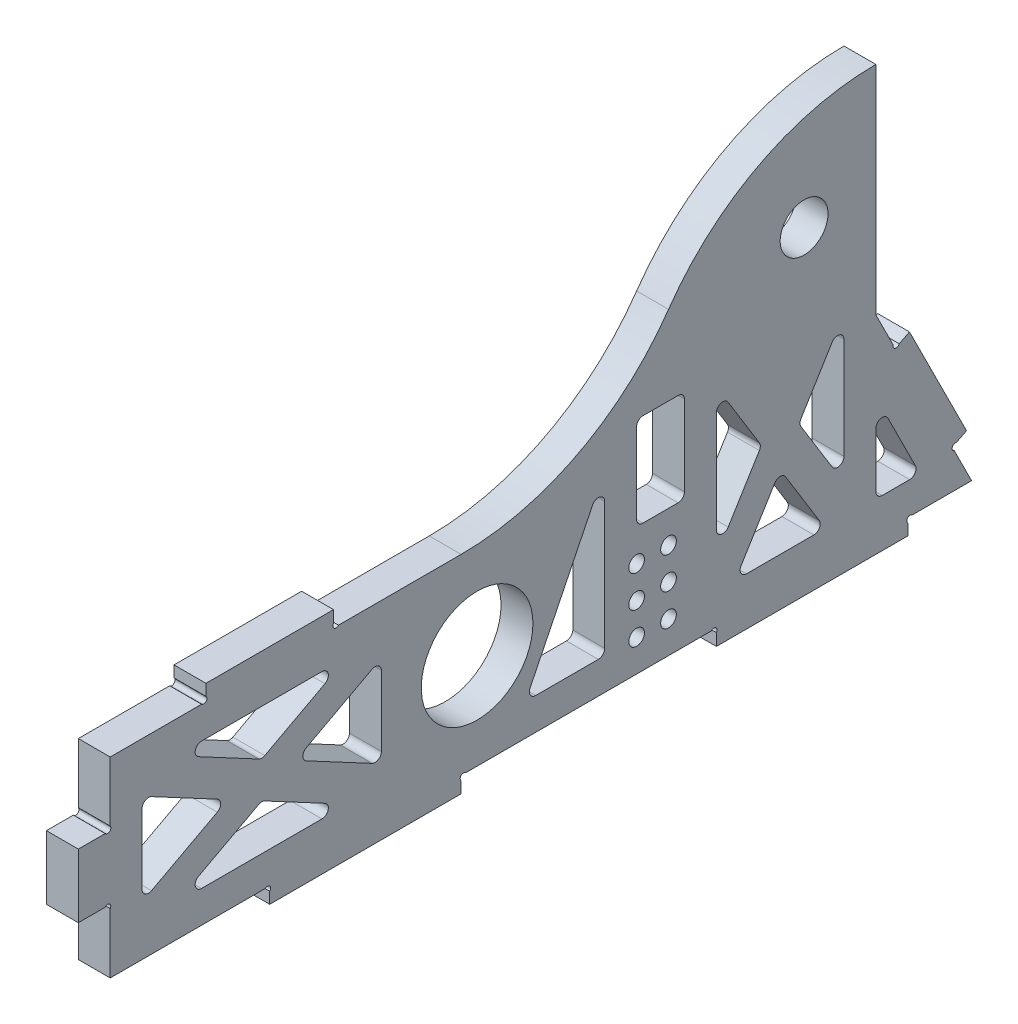
SolidWorks part; units mm, degrees
ref_plane "Front Plane" through (0, 0, 0) normal (0, 0, 1) x (1, 0, 0)
ref_plane "Top Plane" through (0, 0, 0) normal (0, 1, 0) x (1, 0, 0)
ref_plane "Right Plane" through (0, 0, 0) normal (1, 0, 0) x (0, 0, -1)
sketch "Sketch1" plane through (0, 0, 0) normal (1, 0, 0) x (0, 0, -1)
  line L0 (139.7, 38.1) -> (139.7, 124.46)
  line L1 (-177.8, -38.1) -> (177.8, -38.1)
  line L2 (-177.8, -38.1) -> (-177.8, 38.1)
  line L3 (-177.8, 38.1) -> (177.8, 38.1)
  line L4 (177.8, -38.1) -> (177.8, 38.1)
  line L5 (-177.8, -38.1) -> (177.8, 38.1) construction
  line L6 (-177.8, 38.1) -> (177.8, -38.1) construction
  line L7 (139.7, 124.46) -> (-25.4, 38.1)
  line L8 (139.7, 38.1) -> (177.8, -38.1)
  line L9 (-165.1, -38.1) -> (-165.1, 38.1)
  line L11 (-76.2, 38.1) -> (-127, 38.1)
  line L12 (-76.2, 38.1) -> (-76.2, 44.45)
  line L13 (-76.2, 44.45) -> (-127, 44.45)
  line L14 (-127, 38.1) -> (-127, 44.45)
  arc A2 (139.7, 124.46) -> (57.15, 81.28) centre (139.7, 23.9619) ccw
  arc A3 (-25.4, 38.1) -> (57.15, 81.28) centre (-25.4, 138.5981) ccw
  point P0 (0, 0)
  dimension "D6" = 12.7
  dimension "D1" = 50.8
  dimension "D2" = 355.6
  dimension "2" = 76.2
  dimension "D3" = 162.56
  dimension "D4" = 38.1
  dimension "D5" = 152.4
  dimension "D7" = 50.8
  dimension "D8" = 6.35
extrude "Boss-Extrude1" add sketch "Sketch1" along normal blind 12.7
sketch "Sketch2" plane through (12.7, 0, 0) normal (1, 0, 0) x (0, 0, -1)
  line L0 (-165.1, -38.1) -> (177.8, -38.1) construction
  line L1 (139.7, 38.1) -> (139.7, 124.46) construction
  circle A0 centre (111.125, 82.55) radius 9.525
  dimension "D1" = 19.05
  dimension "D2" = 120.65
  dimension "D3" = 28.575
extrude "Cut-Extrude1" cut sketch "Sketch2" against normal through all
sketch "Sketch3" plane through (12.7, 0, 0) normal (1, 0, 0) x (0, 0, -1)
  line L0 (-165.1, -38.1) -> (177.8, -38.1) construction
  line L1 (152.4, -38.1) -> (76.2, -38.1)
  line L2 (152.4, -38.1) -> (152.4, -44.45)
  line L3 (152.4, -44.45) -> (76.2, -44.45)
  line L4 (76.2, -38.1) -> (76.2, -44.45)
  line L5 (-165.1, 38.1) -> (-127, 38.1) construction
  line L6 (-25.4, -38.1) -> (-101.6, -38.1)
  line L7 (-25.4, -38.1) -> (-25.4, -44.45)
  line L8 (-25.4, -44.45) -> (-101.6, -44.45)
  line L9 (-101.6, -38.1) -> (-101.6, -44.45)
  line L10 (-165.1, -38.1) -> (-165.1, 38.1) construction
  line L12 (-165.1, 12.7) -> (-177.8, 12.7)
  line L13 (-165.1, 12.7) -> (-165.1, -12.7)
  line L14 (-165.1, -12.7) -> (-177.8, -12.7)
  line L15 (-177.8, 12.7) -> (-177.8, -12.7)
  dimension "D1" = 6.35
  dimension "D2" = 76.2
  dimension "D3" = 6.35
  dimension "D4" = 76.2
  dimension "D5" = 25.4
  dimension "D6" = 203.2
  dimension "D7" = 12.7
  dimension "D8" = 25.4
  dimension "D9" = 25.4
extrude "Boss-Extrude2" add sketch "Sketch3" against normal blind 12.7
sketch "Sketch9" plane through (12.7, 0, 0) normal (1, 0, 0) x (0, 0, -1)
  line L0 (-25.4, -38.1) -> (76.2, -38.1) construction
  line L1 (-165.1, 12.7) -> (-165.1, 38.1) construction
  circle A0 centre (-19.05, 0) radius 22.225
  dimension "D1" = 44.45
  dimension "D2" = 38.1
  dimension "D3" = 146.05
extrude "Cut-Extrude4" cut sketch "Sketch9" against normal through all
sketch "Sketch12" plane through (12.7, 0, 0) normal (1, 0, 0) x (0, 0, -1)
  line L0 (157.251, -25.4) -> (139.7, 9.7019)
  line L1 (139.7, 9.7019) -> (139.7, -25.4)
  line L2 (139.7, -25.4) -> (157.251, -25.4)
  line L3 (139.7, 38.1) -> (177.8, -38.1) construction
  line L4 (152.4, -38.1) -> (177.8, -38.1) construction
  line L5 (139.7, 38.1) -> (139.7, 124.46) construction
  line L6 (132.408, -22.072) -> (81.608, 60.478)
  line L7 (127, 57.15) -> (76.2, 57.15)
  line L8 (127, 57.15) -> (127, -25.4)
  line L9 (127, -25.4) -> (76.2, -25.4)
  line L10 (76.2, 57.15) -> (76.2, -25.4)
  line L11 (127, 57.15) -> (76.2, -25.4) construction
  line L12 (127, -25.4) -> (76.2, 57.15) construction
  line L13 (121.592, 60.478) -> (70.792, -22.072)
  line L14 (121.592, -28.728) -> (70.792, 53.822)
  line L15 (132.408, 53.822) -> (81.608, -28.728)
  line L16 (101.6, -25.4) -> (101.6, 57.15) construction
  line L20 (-165.1, -38.1) -> (-165.1, -12.7) construction
  line L21 (-57.15, 25.4) -> (-152.4, 25.4)
  line L22 (-57.15, 25.4) -> (-57.15, -25.4)
  line L23 (-57.15, -25.4) -> (-152.4, -25.4)
  line L24 (-152.4, 25.4) -> (-152.4, -25.4)
  line L25 (-57.15, 25.4) -> (-152.4, -25.4) construction
  line L26 (-57.15, -25.4) -> (-152.4, 25.4) construction
  line L27 (-165.1, -38.1) -> (-101.6, -38.1) construction
  line L28 (-60.1382, 31.0029) -> (-155.3882, -19.7971)
  line L29 (-54.1618, -19.7971) -> (-149.4118, 31.0029)
  line L30 (-54.1618, 19.7971) -> (-149.4118, -31.0029)
  line L31 (-60.1382, -31.0029) -> (-155.3882, 19.7971)
  circle A0 centre (111.125, 82.55) radius 9.525 construction
  point P9 (101.6, 15.875)
  point P26 (-104.775, 0)
  dimension "D1" = 12.7
  dimension "D2" = 12.7
  dimension "D3" = 25.4
  dimension "D4" = 12.7
  dimension "D5" = 50.8
  dimension "D8" = 50.8
  dimension "D9" = 95.25
  dimension "D10" = 12.7
  dimension "D11" = 12.7
  dimension "D6" = 6.35
  dimension "D7" = 6.35
  dimension "D12" = 6.35
  dimension "D13" = 6.35
extrude "Cut-Extrude6" cut sketch "Sketch12" against normal through all contours L1 L2 L0 | L8 L15 L6 | L14 L15 L9 | L13 L14 L10 | L22 L30 L29 | L23 L31 L30 | L28 L31 L24 | L29 L28 L21
sketch "Sketch13" plane through (12.7, 0, 0) normal (1, 0, 0) x (0, 0, -1)
  line L0 (63.5, 12.7) -> (44.45, 12.7)
  line L1 (63.5, 12.7) -> (63.5, 49.6981)
  line L2 (63.5, 49.6981) -> (44.45, 49.6981)
  line L3 (44.45, 49.6981) -> (44.45, 12.7)
  line L4 (31.75, -25.4) -> (31.75, 38.737)
  line L5 (31.75, 38.737) -> (0.2157, -25.4)
  line L6 (0.2157, -25.4) -> (31.75, -25.4)
  line L7 (-25.4, -38.1) -> (76.2, -38.1) construction
  line L8 (76.2, 45.0339) -> (76.2, -13.2839) construction
  circle A16 centre (44.45, -25.4) radius 3.127
  circle A29 centre (57.15, -25.4) radius 3.127
  circle A57 centre (44.45, -12.7) radius 3.127
  circle A58 centre (57.15, -12.7) radius 3.127
  circle A61 centre (44.45, 0) radius 3.127
  circle A62 centre (57.15, 0) radius 3.127
  arc A76 (-25.4, 38.1) -> (57.15, 81.28) centre (-25.4, 138.5981) ccw construction
  circle A77 centre (57.15, 12.7) radius 3.127 [skipped]
  circle A78 centre (44.45, 12.7) radius 3.127 [skipped]
  circle A83 centre (44.45, 25.4) radius 3.127 [skipped]
  circle A84 centre (57.15, 25.4) radius 3.127 [skipped]
  dimension "D1" = 50.8
  dimension "D3" = 19.05
  dimension "D2" = 12.7
  dimension "D4" = 12.7
  dimension "D5" = 12.7
  dimension "D7" = 88.9
  dimension "D6" = 5
sketch "Sketch14" plane through (12.7, 0, 0) normal (1, 0, 0) x (0, 0, -1)
  line L0 (147.3908, 22.7185) -> (170.1092, -22.7185)
  line L1 (147.3908, 22.7185) -> (153.0704, 25.5583)
  line L2 (170.1092, -22.7185) -> (175.7888, -19.8786)
  line L3 (153.0704, 25.5583) -> (175.7888, -19.8786)
  line L4 (139.7, 38.1) -> (177.8, -38.1) construction
  line L5 (158.75, 0) -> (192.2502, 16.7501) construction
  dimension "D1" = 6.35
  dimension "D2" = 50.8
extrude "Boss-Extrude3" add sketch "Sketch14" against normal blind 12.7
sketch "Sketch15" plane through (12.7, 0, 0) normal (1, 0, 0) x (0, 0, -1)
  line L0 (170.1092, -22.7185) -> (170.453, -22.833) construction
  line L1 (170.1092, -22.7185) -> (177.8, -38.1) construction
  line L2 (170.1092, -22.7185) -> (175.7888, -19.8786) construction
  line L3 (147.3908, 22.7185) -> (149.5267, 29.1262) construction
  line L4 (153.0704, 25.5583) -> (147.3908, 22.7185) construction
  circle A0 centre (-166.1476, -13.4179) radius 1.27
  circle A2 centre (-127.8675, 39.0275) radius 1.27
  circle A4 centre (-102.4687, -39.0264) radius 1.27
  circle A6 centre (75.2028, -38.8864) radius 1.27
  circle A8 centre (153.2761, -39.0194) radius 1.27
  circle A9 centre (-24.5016, -38.9977) radius 1.27
  circle A10 centre (-166.0964, 13.4875) radius 1.27
  circle A11 centre (-75.2053, 38.8897) radius 1.27
  circle A14 centre (171.3141, -23.1201) radius 1.27
  circle A15 centre (147.7924, 23.9233) radius 1.27
  dimension "D1" = 45
  dimension "D2" = 2.54
  dimension "D3" = 45
extrude "Cut-Extrude8" cut sketch "Sketch15" against normal through all
extrude "Cut-Extrude9" cut sketch "Sketch13" against normal through all
fillet "Fillet1" radius 2.54 24 edges at (6.35, -18.2033, 152.4) (6.35, 18.2033, 152.4) (6.35, 0, 118.2687) (6.35, -25.4, 138.9062) (6.35, -25.4, 70.6437) (6.35, -7.1967, 104.775) (6.35, 0, 91.2812) (6.35, -18.2033, 57.15) (6.35, 25.4, 138.9062) (6.35, 7.1967, 104.775) (6.35, 25.4, 70.6437) (6.35, 18.2033, 57.15) (6.35, 15.875, -94.144) (6.35, -13.2839, -76.2) (6.35, 45.0339, -76.2) (6.35, -25.4, -119.544) (6.35, -25.4, -83.656) (6.35, 3.7589, -101.6) (6.35, -13.2839, -127) (6.35, 15.875, -109.056) (6.35, 45.0339, -127) (6.35, -25.4, -139.7) (6.35, -25.4, -157.251) (6.35, 9.7019, -139.7)
fillet "Fillet2" radius 2.54 7 edges at (6.35, -25.4, -31.75) (6.35, -25.4, -0.2157) (6.35, 38.737, -31.75) (6.35, 12.7, -63.5) (6.35, 12.7, -44.45) (6.35, 49.6981, -44.45) (6.35, 49.6981, -63.5)
